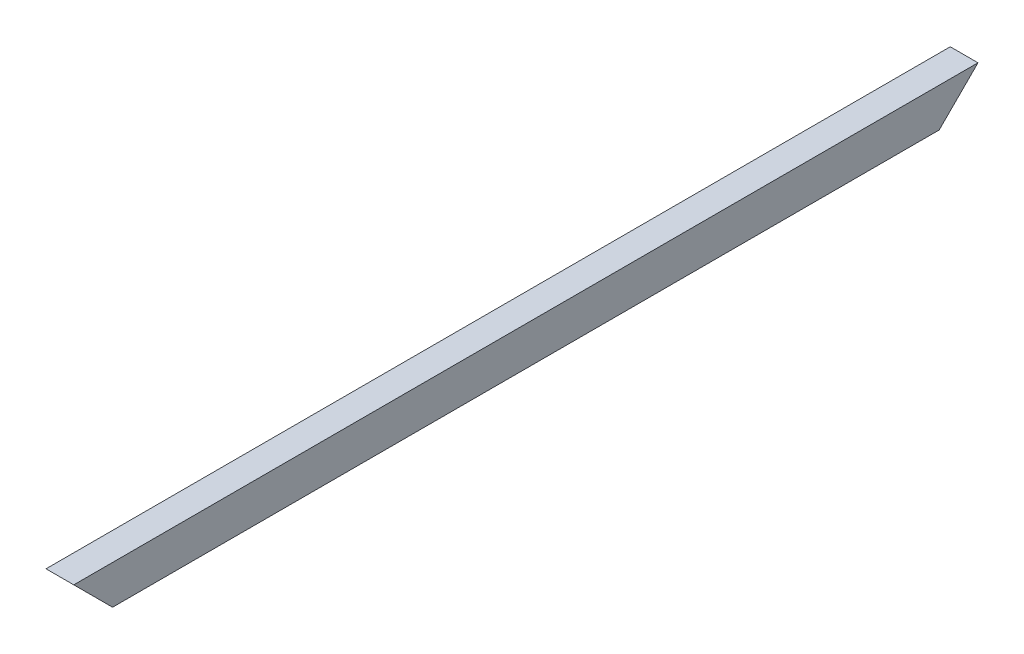
SolidWorks part; units mm, degrees
ref_plane "Front" through (0, 0, 0) normal (0, 0, 1) x (1, 0, 0)
ref_plane "Top" through (0, 0, 0) normal (0, 1, 0) x (1, 0, 0)
ref_plane "Right" through (0, 0, 0) normal (1, 0, 0) x (0, 0, -1)
other "Configuration Table"
sketch "Sketch1" plane through (0, 0, 0) normal (0, 0, 1) x (1, 0, 0)
  line L0 (17.8891, 87.0445) -> (-1.4538, 87.0445)
  line L1 (-1.4538, 87.0445) -> (-1.4538, 80.352)
  line L2 (2.4111, 76.487) -> (2.4111, 73.5278)
  line L3 (14.2157, 60.0081) -> (17.8891, 60.0081)
  line L4 (17.8891, 60.0081) -> (17.8891, 87.0445)
  line L5 (7.688, 69.7412) -> (7.688, 66.9611)
  arc A0 (-1.4538, 80.352) -> (2.4111, 76.487) centre (2.4111, 80.352) ccw
  arc A1 (2.4111, 73.5278) -> (7.688, 69.7412) centre (2.4111, 67.9577) cw
  arc A2 (7.688, 66.9611) -> (14.2157, 60.0081) centre (14.6549, 66.9611) ccw
extrude "Base-Extrude" add sketch "Sketch1" along normal mid plane 630
sketch "Sketch2" plane through (0, 0, 0) normal (1, 0, 0) x (0, 0, -1)
  line L0 (315, 87.0445) -> (255, 27.0445)
  line L1 (255, 27.0445) -> (315, 27.0445)
  line L2 (315, 27.0445) -> (315, 87.0445)
  point P1 (315, 87.0445)
  dimension "D1" = 45
  dimension "D2" = 60
extrude "Cut-Extrude1" cut sketch "Sketch2" against normal through all and the other way through all
mirror "Mirror1" about plane through (0, 0, 0) normal (0, 0, 1) of "Cut-Extrude1"
